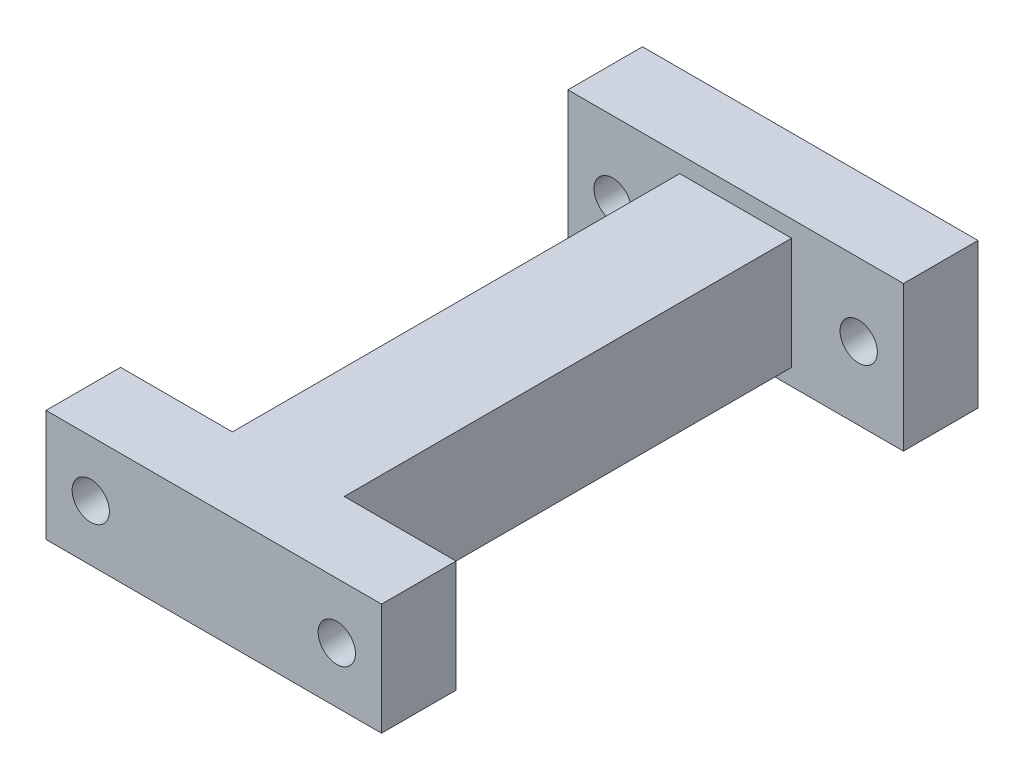
SolidWorks part; units mm, degrees
ref_plane "前视基准面" through (0, 0, 0) normal (0, 0, 1) x (1, 0, 0)
ref_plane "上视基准面" through (0, 0, 0) normal (0, 1, 0) x (1, 0, 0)
ref_plane "右视基准面" through (0, 0, 0) normal (1, 0, 0) x (0, 0, -1)
sketch "草图1" plane through (0, 0, 0) normal (0, 0, 1) x (1, 0, 0)
  line L1 (7.5, -7.5) -> (-7.5, -7.5)
  line L2 (7.5, -7.5) -> (7.5, 7.5)
  line L3 (7.5, 7.5) -> (-7.5, 7.5)
  line L4 (-7.5, -7.5) -> (-7.5, 7.5)
  line L5 (7.5, -7.5) -> (-7.5, 7.5) construction
  line L6 (7.5, 7.5) -> (-7.5, -7.5) construction
  point P0 (0, 0)
  dimension "D1" = 15
  dimension "D2" = 15
extrude "凸台-拉伸1" add sketch "草图1" along normal blind 80
sketch "草图2" plane through (0, 0, 80) normal (0, 0, 1) x (1, 0, 0)
  line L1 (22.5, -7.5) -> (-22.5, -7.5)
  line L2 (22.5, -7.5) -> (22.5, 7.5)
  line L3 (22.5, 7.5) -> (-22.5, 7.5)
  line L4 (-22.5, -7.5) -> (-22.5, 7.5)
  line L5 (22.5, -7.5) -> (-22.5, 7.5) construction
  line L6 (22.5, 7.5) -> (-22.5, -7.5) construction
  point P0 (0, 0)
  dimension "D1" = 15
  dimension "D2" = 45
extrude "凸台-拉伸2" add sketch "草图2" against normal blind 10
sketch "草图3" plane through (0, 0, 80) normal (0, 0, 1) x (1, 0, 0)
  line L0 (-22.5, 7.5) -> (-22.5, -7.5) construction
  line L2 (0, -55) -> (0, 55) construction
  circle A0 centre (-16.5, 0) radius 2.5
  circle A1 centre (16.5, 0) radius 2.5
  dimension "D1" = 6
  dimension "D2" = 5
extrude "切除-拉伸1" cut sketch "草图3" against normal blind 20
sketch "草图5" plane through (0, 0, 0) normal (0, 0, -1) x (-1, 0, 0)
  line L1 (22.5, -9.7364) -> (-22.5, -9.7364)
  line L2 (22.5, -9.7364) -> (22.5, 9.7364)
  line L3 (22.5, 9.7364) -> (-22.5, 9.7364)
  line L4 (-22.5, -9.7364) -> (-22.5, 9.7364)
  line L5 (22.5, -9.7364) -> (-22.5, 9.7364) construction
  line L6 (22.5, 9.7364) -> (-22.5, -9.7364) construction
  point P0 (0, 0)
  dimension "D1" = 45
extrude "凸台-拉伸3" add sketch "草图5" against normal blind 10
sketch "草图6" plane through (0, 0, 0) normal (0, 0, -1) x (-1, 0, 0)
  line L0 (-22.5, 9.7364) -> (-22.5, -9.7364) construction
  line L1 (22.5, -9.7364) -> (22.5, 9.7364) construction
  circle A0 centre (-16.5, 0) radius 2.5
  circle A1 centre (16.5, 0) radius 2.5
  point P6 (-22.5, 0)
  point P9 (22.5, 0)
  dimension "D1" = 6
  dimension "D3" = 5
  dimension "D4" = 5
  dimension "D2" = 6
extrude "切除-拉伸2" cut sketch "草图6" against normal through all
